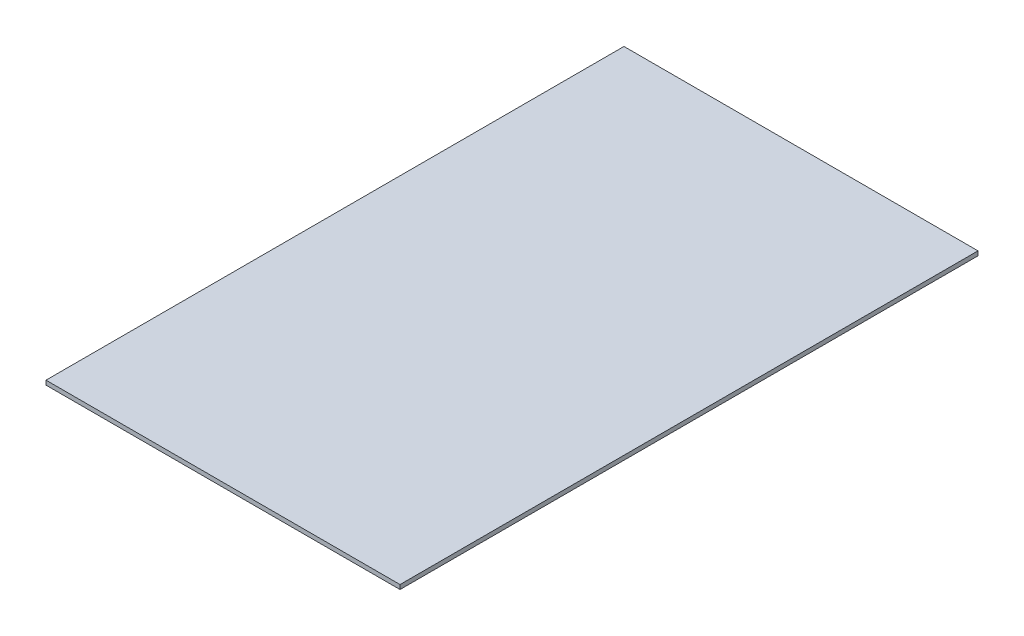
SolidWorks part; units mm, degrees
ref_plane "Front Plane" through (0, 0, 0) normal (0, 0, 1) x (1, 0, 0)
ref_plane "Top Plane" through (0, 0, 0) normal (0, 1, 0) x (1, 0, 0)
ref_plane "Right Plane" through (0, 0, 0) normal (1, 0, 0) x (0, 0, -1)
sketch "Sketch2" plane through (0, 0, 0) normal (0, 1, 0) x (1, 0, 0)
  line L1 (0, 0) -> (245, 0)
  line L2 (0, 0) -> (0, 400)
  line L3 (0, 400) -> (245, 400)
  line L4 (245, 0) -> (245, 400)
  dimension "D1" = 400
  dimension "D2" = 245
extrude "Boss-Extrude1" add sketch "Sketch2" along normal blind 3
